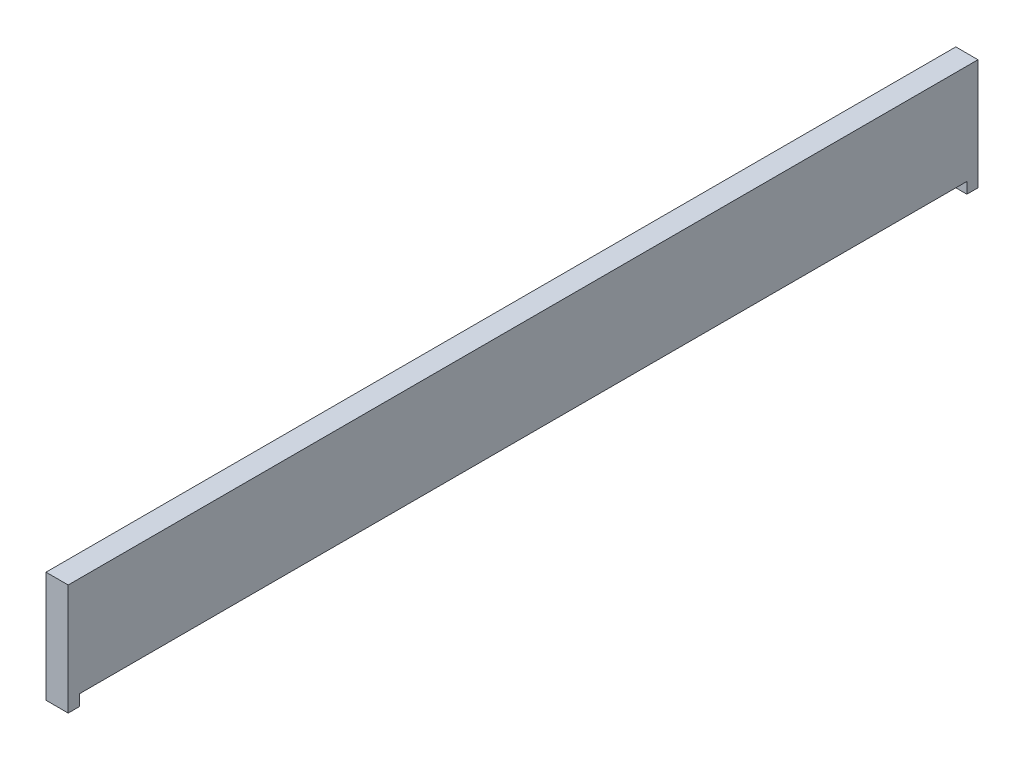
SolidWorks part; units mm, degrees
material "Сосна"
ref_plane "Спереди" through (0, 0, 0) normal (0, 0, 1) x (1, 0, 0)
ref_plane "Сверху" through (0, 0, 0) normal (0, 1, 0) x (1, 0, 0)
ref_plane "Справа" through (0, 0, 0) normal (1, 0, 0) x (0, 0, -1)
sketch "Эскиз1" plane through (0, 0, 0) normal (0, 0, 1) x (1, 0, 0)
  line L0 (0, 0) -> (0, 100)
  line L3 (0, 100) -> (20, 100)
  line L4 (20, 100) -> (20, 10)
  line L5 (20, 10) -> (10, 10)
  line L6 (10, 10) -> (10, 0)
  line L7 (10, 0) -> (0, 0)
  dimension "D1" = 100
  dimension "D2" = 20
  dimension "D3" = 10
  dimension "D4" = 10
extrude "Бобышка-Вытянуть1" add sketch "Эскиз1" along normal blind 820
sketch "Эскиз3" plane through (10, 0, 0) normal (1, 0, 0) x (0, 0, -1)
  line L0 (-820, 10) -> (0, 10) construction
  line L1 (-820, 0) -> (-810, 0)
  line L2 (-820, 0) -> (-820, 10)
  line L3 (-820, 10) -> (-810, 10)
  line L4 (-810, 0) -> (-810, 10)
  line L5 (-410, 0) -> (-410, 110.6456) construction
  line L7 (-820, 0) -> (0, 0) construction
  line L8 (-10, 0) -> (-10, 10)
  line L9 (0, 10) -> (-10, 10)
  line L10 (0, 0) -> (0, 10)
  line L11 (0, 0) -> (-10, 0)
  dimension "D1" = 10
extrude "Бобышка-Вытянуть2" add sketch "Эскиз3" along normal blind 10
